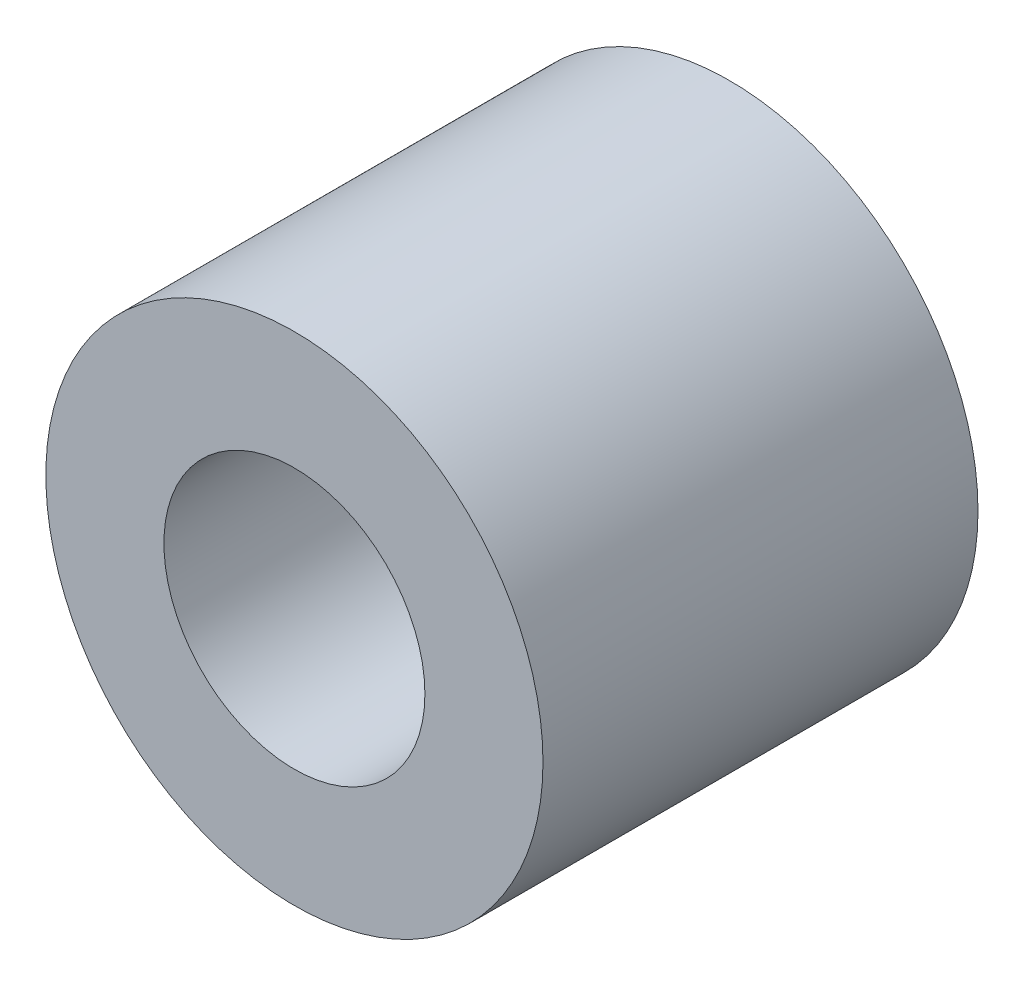
SolidWorks part; units mm, degrees
ref_plane "Front Plane" through (0, 0, 0) normal (0, 0, 1) x (1, 0, 0)
ref_plane "Top Plane" through (0, 0, 0) normal (0, 1, 0) x (1, 0, 0)
ref_plane "Right Plane" through (0, 0, 0) normal (1, 0, 0) x (0, 0, -1)
sketch "Sketch1" plane through (0, 0, 0) normal (0, 0, 1) x (1, 0, 0)
  circle A0 centre (0, 0) radius 4
extrude "Boss-Extrude1" add sketch "Sketch1" along normal blind 7
sketch "Sketch2" plane through (0, 0, 7) normal (0, 0, 1) x (1, 0, 0)
  circle A0 centre (0, 0) radius 2.1
extrude "Cut-Extrude1" cut sketch "Sketch2" against normal through all
